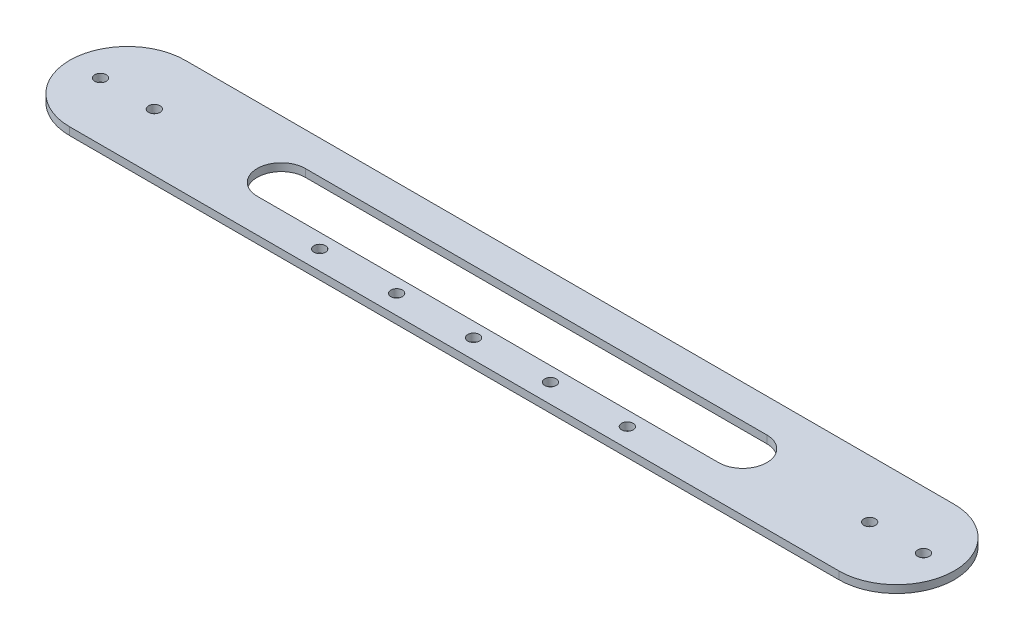
SolidWorks part; units mm, degrees
ref_plane "前视基准面" through (0, 0, 0) normal (0, 0, 1) x (1, 0, 0)
ref_plane "上视基准面" through (0, 0, 0) normal (0, 1, 0) x (1, 0, 0)
ref_plane "右视基准面" through (0, 0, 0) normal (1, 0, 0) x (0, 0, -1)
other "Configuration Table"
sketch "草图1" plane through (0, 0, 0) normal (0, 1, 0) x (1, 0, 0)
  line L0 (-100, 0) -> (100, 0) construction
  line L1 (-100, 15) -> (100, 15)
  line L2 (-100, -15) -> (100, -15)
  arc A0 (-100, 15) -> (-100, -15) centre (-100, 0) ccw
  arc A1 (100, -15) -> (100, 15) centre (100, 0) ccw
  point P2 (0, 0)
  dimension "D1" = 200
  dimension "D2" = 30
extrude "凸台-拉伸1" add sketch "草图1" along normal blind 2
sketch "草图4" plane through (0, 2, 0) normal (0, 1, 0) x (1, 0, 0)
  line L0 (-121.5103, 0) -> (132.2252, 0) construction
  line L1 (0, 17.8852) -> (0, -20.5529) construction
  line L2 (-60, 0) -> (60, 0) construction
  line L3 (-60, 6.25) -> (60, 6.25)
  line L4 (-60, -6.25) -> (60, -6.25)
  line L5 (-100, -15) -> (100, -15) construction
  circle A0 centre (-100, 0) radius 7 construction
  circle A1 centre (-107, 0) radius 1.5
  circle A2 centre (-93, 0) radius 1.5
  circle A3 centre (100, 0) radius 7 construction
  circle A4 centre (107, 0) radius 1.5
  circle A5 centre (93, 0) radius 1.5
  arc A6 (-60, 6.25) -> (-60, -6.25) centre (-60, 0) ccw
  arc A7 (60, -6.25) -> (60, 6.25) centre (60, 0) ccw
  circle A8 centre (0, -10) radius 1.5
  circle A9 centre (20, -10) radius 1.5
  circle A10 centre (40, -10) radius 1.5
  circle A11 centre (-20, -10) radius 1.5
  circle A12 centre (-40, -10) radius 1.5
  point P20 (0, 0)
  point P30 (0, 0)
  dimension "D1" = 14
  dimension "D2" = 3
  dimension "D3" = 3
  dimension "D6" = 3
  dimension "D4" = 120
  dimension "D5" = 12.5
  dimension "D7" = 5
  dimension "D9" = 20
  dimension "D10" = 20
  dimension "D8" = 3
extrude "切除-拉伸1" cut sketch "草图4" against normal blind 2
